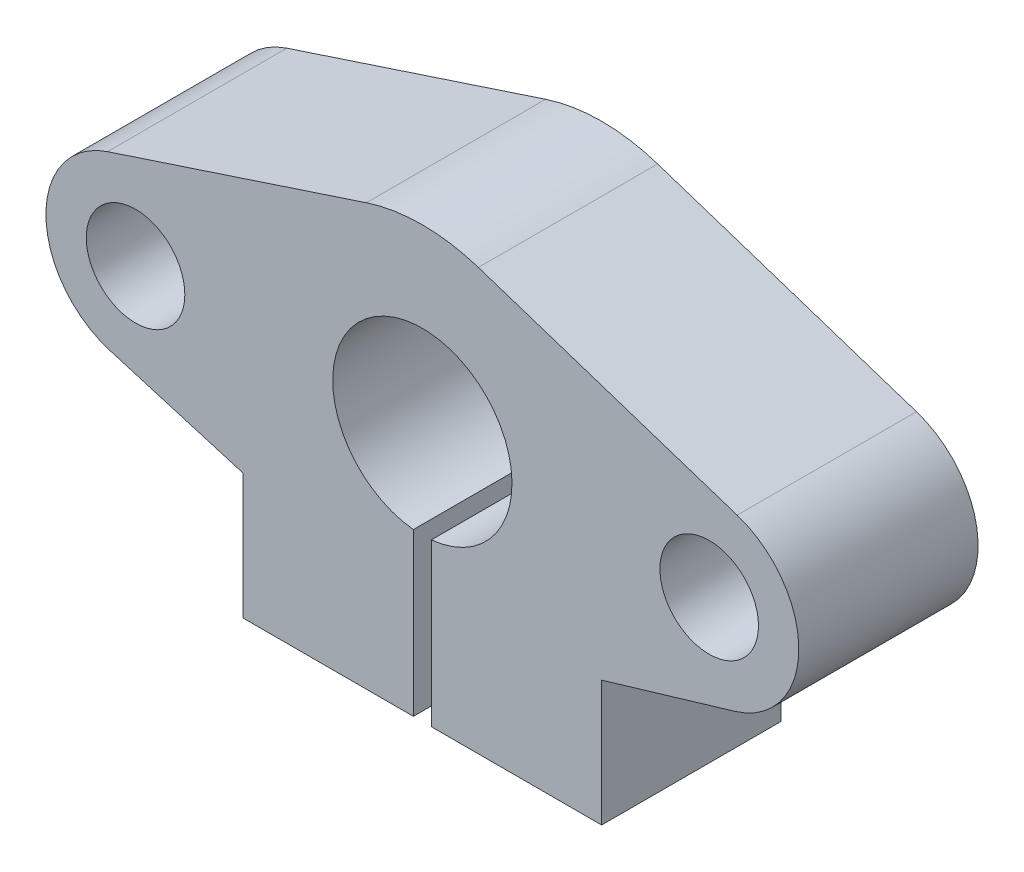
SolidWorks part; units mm, degrees
ref_plane "前视基准面" through (0, 0, 0) normal (0, 0, 1) x (1, 0, 0)
ref_plane "上视基准面" through (0, 0, 0) normal (0, 1, 0) x (1, 0, 0)
ref_plane "右视基准面" through (0, 0, 0) normal (1, 0, 0) x (0, 0, -1)
sketch "草图1" plane through (0, 0, 0) normal (0, 0, 1) x (1, 0, 0)
  line L0 (-39.2173, 0) -> (36.0917, 0) construction
  line L1 (0, 30.4168) -> (0, -14) construction
  line L2 (-17.5625, 4.7496) -> (-3.125, 9.4992)
  line L3 (3.125, 9.4992) -> (17.5625, 4.7496)
  line L4 (-10, -7) -> (-17.4248, -4.7927)
  line L5 (-10, -14) -> (-10, -7)
  line L6 (-0.5, -4.9749) -> (-0.5, -9.9875)
  line L7 (0.5, -4.9749) -> (0.5, -9.9875)
  line L8 (-0.5, -7.4812) -> (0, -7.4812)
  line L9 (0, -7.4812) -> (0.5, -7.4812)
  line L10 (-10, -14) -> (10, -14)
  line L11 (10, -7) -> (17.4248, -4.7927)
  line L12 (10, -14) -> (10, -7)
  line L13 (-0.5, -9.9875) -> (-0.5, -14)
  line L14 (0.5, -9.9875) -> (0.5, -14)
  circle A0 centre (0, 0) radius 5
  circle A1 centre (-16, 0) radius 2.75
  circle A2 centre (16, 0) radius 2.75
  circle A3 centre (0, 0) radius 10
  circle A4 centre (-16, 0) radius 5
  circle A5 centre (16, 0) radius 5
  dimension "D1" = 10
  dimension "D2" = 5.5
  dimension "D5" = 20
  dimension "D6" = 10
  dimension "D3" = 16
  dimension "D4" = 32
  dimension "D7" = 1
  dimension "D8" = 14
  dimension "D9" = 20
  dimension "D10" = 7
extrude "凸台-拉伸1" add sketch "草图1" along normal blind 10
